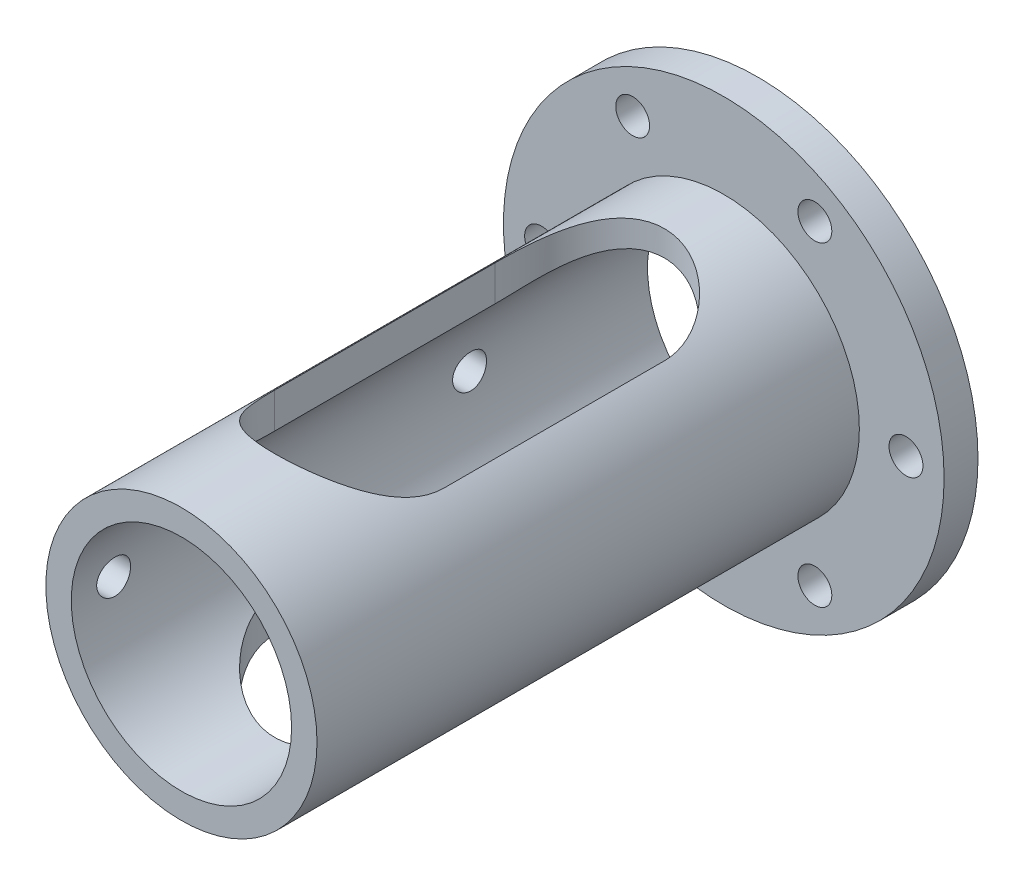
SolidWorks part; units mm, degrees
ref_plane "Front Plane" through (0, 0, 0) normal (0, 0, 1) x (1, 0, 0)
ref_plane "Top Plane" through (0, 0, 0) normal (0, 1, 0) x (1, 0, 0)
ref_plane "Right Plane" through (0, 0, 0) normal (1, 0, 0) x (0, 0, -1)
sketch "Sketch1" plane through (0, 0, 0) normal (0, 0, 1) x (1, 0, 0)
  line L0 (0, 26) -> (0, 0) construction
  circle A0 centre (0, 0) radius 26
  circle A7 centre (0, 0) radius 13
  circle A9 centre (-21.5, 0) radius 2
  circle A10 centre (-10.75, 18.6195) radius 2
  circle A11 centre (10.75, 18.6195) radius 2
  circle A12 centre (21.5, 0) radius 2
  circle A13 centre (10.75, -18.6195) radius 2
  circle A14 centre (-10.75, -18.6195) radius 2
  point P18 (0, 0)
  point P21 (0, 0)
  dimension "D1" = 52
  dimension "D2" = 6
  dimension "D5" = 26
  dimension "D6" = 4
  dimension "D7" = 21.5
extrude "Boss-Extrude1" add sketch "Sketch1" along normal blind 4
sketch "Sketch2" plane through (0, 0, 4) normal (0, 0, 1) x (1, 0, 0)
  circle A0 centre (0, 0) radius 13
  circle A1 centre (0, 0) radius 16
  dimension "D1" = 32
extrude "Boss-Extrude2" add sketch "Sketch2" along normal blind 64
sketch "Sketch3" plane through (0, 0, 0) normal (0, 1, 0) x (1, 0, 0)
  line L0 (0, -21) -> (0, -47) construction
  line L1 (10, -21) -> (10, -47)
  line L2 (-10, -21) -> (-10, -47)
  line L3 (-16, -4) -> (16, -4) construction
  arc A0 (10, -21) -> (-10, -21) centre (0, -21) ccw
  arc A1 (-10, -47) -> (10, -47) centre (0, -47) ccw
  point P3 (0, -34)
  dimension "D2" = 10
  dimension "D1" = 26
  dimension "D3" = 17
extrude "Cut-Extrude1" cut sketch "Sketch3" against normal mid plane 64
sketch "Sketch4" plane through (0, 0, 0) normal (1, 0, 0) x (0, 0, -1)
  line L0 (-4, 16) -> (-4, -16) construction
  circle A0 centre (-21, 0) radius 2
  circle A1 centre (-63, 0) radius 2
  dimension "D1" = 4
  dimension "D2" = 4
  dimension "D3" = 17
  dimension "D4" = 42
extrude "Cut-Extrude2" cut sketch "Sketch4" against normal blind 64
